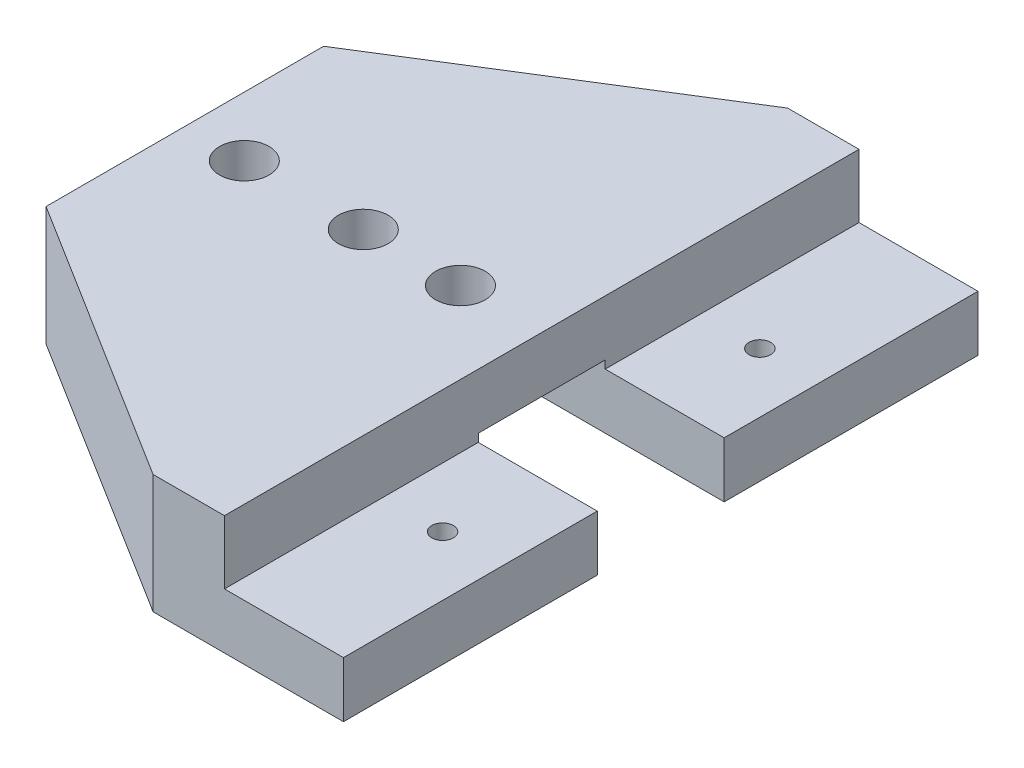
SolidWorks part; units mm, degrees
ref_plane "Front" through (0, 0, 0) normal (0, 0, 1) x (1, 0, 0)
ref_plane "Top" through (0, 0, 0) normal (0, 1, 0) x (1, 0, 0)
ref_plane "Right" through (0, 0, 0) normal (1, 0, 0) x (0, 0, -1)
sketch "Sketch1" plane through (0, 0, 0) normal (0, 1, 0) x (1, 0, 0)
  line L0 (-60.96, 22.225) -> (-60.96, -22.225)
  line L1 (-60.96, -22.225) -> (-15.24, -50.8)
  line L2 (-15.24, -50.8) -> (15.24, -50.8)
  line L3 (15.24, -50.8) -> (15.24, 50.8)
  line L4 (15.24, 50.8) -> (-15.24, 50.8)
  line L5 (-15.24, 50.8) -> (-60.96, 22.225)
  line L6 (-50, 0) -> (50, 0) construction
  line L7 (0, -50) -> (0, 50) construction
  point P6 (-60.96, 0)
  point P9 (15.24, 0)
  point P10 (0, 50.8)
  dimension "D1" = 76.2
  dimension "D2" = 101.6
  dimension "D3" = 44.45
  dimension "D4" = 30.48
extrude "Boss-Extrude1" add sketch "Sketch1" along normal mid plane 19.05 contours L3 L4 L5 L0 L1 L2
sketch "Sketch2" plane through (0, -9.525, 0) normal (0, -1, 0) x (1, 0, 0)
  line L0 (-60.96, -22.225) -> (-60.96, 22.225) construction
  line L1 (-60.96, -10.16) -> (15.24, -10.16)
  line L2 (-60.96, -10.16) -> (-60.96, 10.16)
  line L3 (-60.96, 10.16) -> (15.24, 10.16)
  line L4 (15.24, -10.16) -> (15.24, 10.16)
  line L5 (15.24, 50.8) -> (15.24, -50.8) construction
  line L6 (50, 0) -> (-50, 0) construction
  point P8 (15.24, 0)
  point P11 (8.3117, 28.5962)
  point P12 (8.3117, -19.4929)
  point P13 (0, 0)
  dimension "D1" = 20.32
extrude "Cut-Extrude1" cut sketch "Sketch2" against normal blind 10.16
sketch "Sketch3" plane through (0, 9.525, 0) normal (0, 1, 0) x (1, 0, 0)
  line L0 (15.24, 50.8) -> (-15.24, 50.8) construction
  line L1 (15.24, -50.8) -> (-3.81, -50.8)
  line L2 (15.24, -50.8) -> (15.24, 50.8)
  line L3 (15.24, 50.8) -> (-3.81, 50.8)
  line L4 (-3.81, -50.8) -> (-3.81, 50.8)
  dimension "D1" = 19.05
extrude "Cut-Extrude2" cut sketch "Sketch3" against normal blind 10.16 contours L4 L3 L2 L1
sketch "Sketch4" plane through (0, 9.525, 0) normal (0, 1, 0) x (1, 0, 0)
  line L0 (-50, 0) -> (50, 0) construction
  line L1 (-60.96, 22.225) -> (-60.96, -22.225) construction
  point P0 (-16.8275, 0)
  point P1 (-32.385, 0)
  point P4 (-51.435, 0)
  dimension "D1" = 19.05
  dimension "D2" = 9.525
  dimension "D3" = 15.5575
hole_wizard "5/16 (0.3125) Diameter Hole1" positions "Sketch5" profile "Sketch6" hole size "5/16" standard "ANSI Inch" end condition through all
sketch "Sketch5" plane through (0, 9.525, 0) normal (0, 1, 0) x (1, 0, 0)
  point P0 (-51.435, 0)
  point P3 (-32.385, 0)
  point P6 (-16.8275, 0)
sketch "Sketch6" plane through (-51.435, 9.525, 0) normal (1, 0, 0) x (0, 0, 1)
  line L0 (0, 0) -> (0, 19.05)
  line L1 (0, 19.05) -> (3.9687, 19.05)
  line L2 (3.9687, 19.05) -> (3.9687, 0)
  line L5 (3.9687, 0) -> (0, 0)
  line L11 (0, -6.35) -> (0, 107.95) construction
  dimension "Thru Hole Dia." = 7.9375
  dimension "Thru Hole Depth" = 19.05
sketch "Sketch7" plane through (0, -9.525, 0) normal (0, -1, 0) x (1, 0, 0)
  line L0 (5.715, 25.4) -> (5.715, -25.4) construction
  line L1 (50, 0) -> (-50, 0) construction
  line L2 (15.24, -10.16) -> (15.24, -50.8) construction
  point P0 (5.715, 25.4)
  point P1 (5.715, -25.4)
  point P4 (5.715, 0)
  dimension "D1" = 50.8
  dimension "D2" = 9.525
hole_wizard "#8-32 Tapped Hole1" positions "Sketch8" profile "Sketch10" tap size "#8-32" standard "ANSI Inch" end condition through all
sketch "Sketch8" plane through (0, -9.525, 0) normal (0, -1, 0) x (-1, 0, 0)
  point P0 (-5.715, -25.4)
  point P3 (-5.715, 25.4)
sketch "Sketch10" plane through (5.715, -9.525, 25.4) normal (1, 0, 0) x (0, 0, -1)
  line L0 (0, 0) -> (0, 19.05)
  line L1 (0, 19.05) -> (1.7272, 19.05)
  line L2 (1.7272, 19.05) -> (1.7272, 0)
  line L5 (1.7272, 0) -> (0, 0)
  line L11 (0, -6.35) -> (0, 107.95) construction
  dimension "Thru Tap Drill Dia." = 3.4544
  dimension "Thru Tap Drill Depth" = 19.05
cosmetic thread "Hole Thread1" parameters "D2"=4.1656
cosmetic thread "Hole Thread2" parameters "D2"=4.1656
